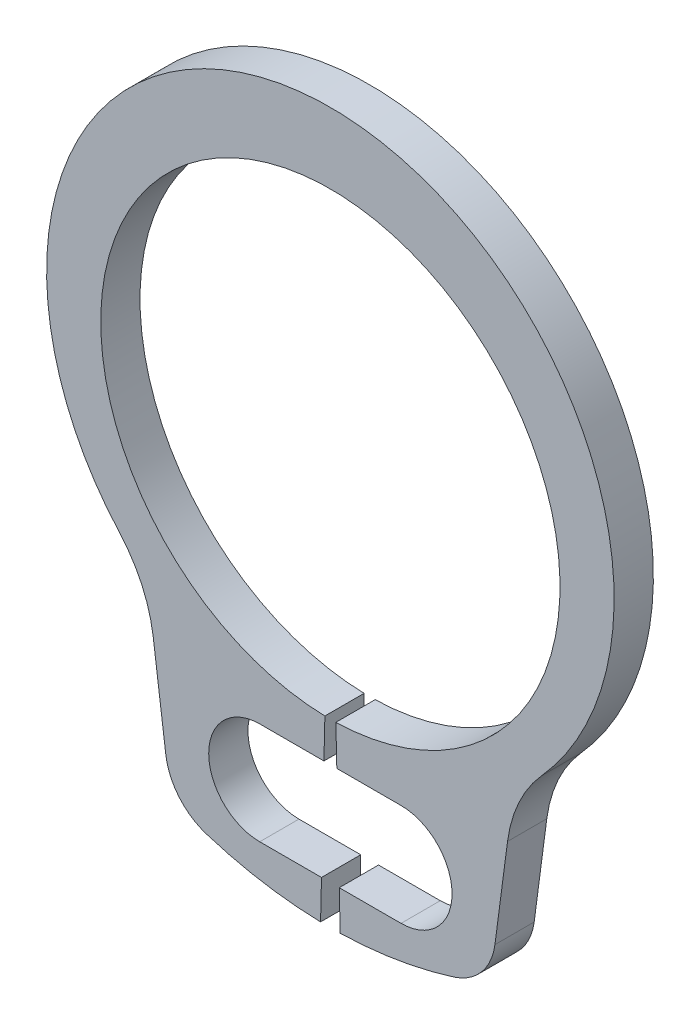
SolidWorks part; units mm, degrees
ref_plane "Plane1" through (0, 0, 0) normal (0, 0, 1) x (1, 0, 0)
ref_plane "Plane2" through (0, 0, 0) normal (0, 1, 0) x (1, 0, 0)
ref_plane "Plane3" through (0, 0, 0) normal (1, 0, 0) x (0, 0, -1)
sketch "Clipboard" plane through (0, 0, 0) normal (0, 0, 1) x (1, 0, 0)
  line L0 (0, 0) -> (0.4572, 0)
  line L1 (0, 0) -> (0, 0.2794)
  line L2 (0, 0) -> (0, -1.1684)
  circle A0 centre (0, 0) radius 0.3302
  circle A1 centre (0, 0) radius 1.5875
  dimension "HoleDia" = 0.6604
  dimension "ShaftDia" = 3.175
  dimension "LargeSection" = 0.4572
  dimension "SmallSection" = 0.2794
  dimension "LugSection" = 1.1684
sketch "BodySke" plane through (0, 0, 0) normal (0, 0, 1) x (1, 0, 0)
  line L0 (-1.5431, 0) -> (1.5431, 0) construction
  line L1 (0, 0) -> (0, 1.9431) construction
  line L2 (0.0355, -1.4855) -> (0.0635, -2.6535)
  line L3 (-0.0355, -1.4855) -> (-0.0635, -2.6535)
  line L4 (0, 0) -> (2.0272, -1.7134) construction
  line L5 (0, 0) -> (-2.0272, -1.7134) construction
  line L7 (1.1464, -1.5974) -> (1.0649, -2.2167)
  line L8 (-1.1464, -1.5974) -> (-1.0649, -2.2167)
  circle A0 centre (0, 0) radius 1.4859 construction
  arc A1 (0.0355, -1.4855) -> (-0.0355, -1.4855) centre (0, 0) ccw
  arc A2 (1.3482, -1.1395) -> (-1.3482, -1.1395) centre (0, 0.1069) ccw construction
  arc A3 (0.0635, -2.6535) -> (0.8023, -2.5301) centre (0, 0) ccw
  arc A4 (1.3662, -1.1198) -> (1.1464, -1.5974) centre (2.0272, -1.7134) ccw
  arc A5 (-1.1464, -1.5974) -> (-1.3662, -1.1198) centre (-2.0272, -1.7134) ccw
  arc A6 (-0.8023, -2.5301) -> (-0.0635, -2.6535) centre (0, 0) ccw
  arc A7 (1.3662, -1.1198) -> (-1.3662, -1.1198) centre (0, 0.1069) ccw
  arc A8 (-1.1196, -1.8013) -> (1.1196, -1.8013) centre (0, 0) ccw construction
  circle A9 centre (0.4572, -2.071) radius 0.3302
  circle A10 centre (-0.4572, -2.071) radius 0.3302
  arc A11 (1.0649, -2.2167) -> (0.8023, -2.5301) centre (0.6871, -2.167) cw
  arc A12 (-1.0649, -2.2167) -> (-0.8023, -2.5301) centre (-0.6871, -2.167) ccw
  point P28 (1.0349, -2.4442)
  point P31 (-1.0349, -2.4442)
  dimension "GrooveDia" = 2.9718
  dimension "LugRad" = 2.6543
  dimension "HoleOffsetRad" = 2.1209
  dimension "HoleDia" = 0.6604
  dimension "D3" = 0.381
  dimension "LargeRad" = 1.9431
  dimension "SmallRad" = 1.7653
  dimension "SmallAngle" = 99.591
  dimension "D2" = 15
  dimension "HoleSpacing" = 0.9144
  dimension "Gap" = 0.127
extrude "Body" add sketch "BodySke" against normal blind 0.254
sketch "NotSke" plane through (0, 0, 0) normal (0, 0, 1) x (1, 0, 0)
  line L0 (0.4572, -1.7408) -> (0.4572, -2.4012)
  line L1 (0.4572, -2.4012) -> (-0.4572, -2.4012)
  line L2 (-0.4572, -2.4012) -> (-0.4572, -1.7408)
  line L3 (-0.4572, -1.7408) -> (0.4572, -1.7408)
  circle A0 centre (0.4572, -2.071) radius 0.3302 construction
  circle A1 centre (-0.4572, -2.071) radius 0.3302 construction
extrude "Notch" cut sketch "NotSke" against normal through all
equation "' \"ShaftDia@Clipboard\" = 0.125"
equation "' \"Thickness@Body\" = 0.01"
equation "' \"GrooveDia@BodySke\" = 0.117"
equation "' \"LugSection@Clipboard\" = 0.046"
equation "' \"LargeSection@Clipboard\" = 0.018"
equation "' \"SmallSection@Clipboard\" = 0.011"
equation "' \"HoleDia@Clipboard\" = 0.026"
equation "' \"ShaftDia@Clipboard\" = 0.394"
equation "' \"Thickness@Body\" = 0.025"
equation "' \"GrooveDia@BodySke\" = 0.369"
equation "' \"LugSection@Clipboard\" = 0.087"
equation "' \"LargeSection@Clipboard\" = 0.052"
equation "' \"SmallSection@Clipboard\" = 0.031"
equation "' \"HoleDia@Clipboard\" = 0.041"
equation "\"Gap@BodySke\" =  \"Thickness@Body\" / 2"
equation "\"LargeRad@BodySke\" =  \"GrooveDia@BodySke\" / 2 +  \"LargeSection@Clipboard\""
equation "\"SmallRad@BodySke\" =  \"GrooveDia@BodySke\" / 2 +  \"SmallSection@Clipboard\""
equation "\"LugRad@BodySke\" = \"GrooveDia@BodySke\" / 2 + \"LugSection@Clipboard\""
equation "\"HoleOffsetRad@BodySke\" = (  \"ShaftDia@Clipboard\" / 2 + \"LugRad@BodySke\" ) / 2"
equation "\"HoleSpacing@BodySke\" = \"Gap@BodySke\"  * 2 +  \"HoleDia@Clipboard\""
equation "\"HoleDia@BodySke\" =  \"HoleDia@Clipboard\""
equation "\"SmallAngle@BodySke\" = atn(\"HoleSpacing@BodySke\" / 2 / sqr(\"HoleOffsetRad@BodySke\"  * \"HoleOffsetRad@BodySke\" - (\"HoleSpacing@BodySke\" / 2) * (\"HoleSpacing@BodySke\" / 2) ))  * 8 * ( 180 / 3.141593)"
